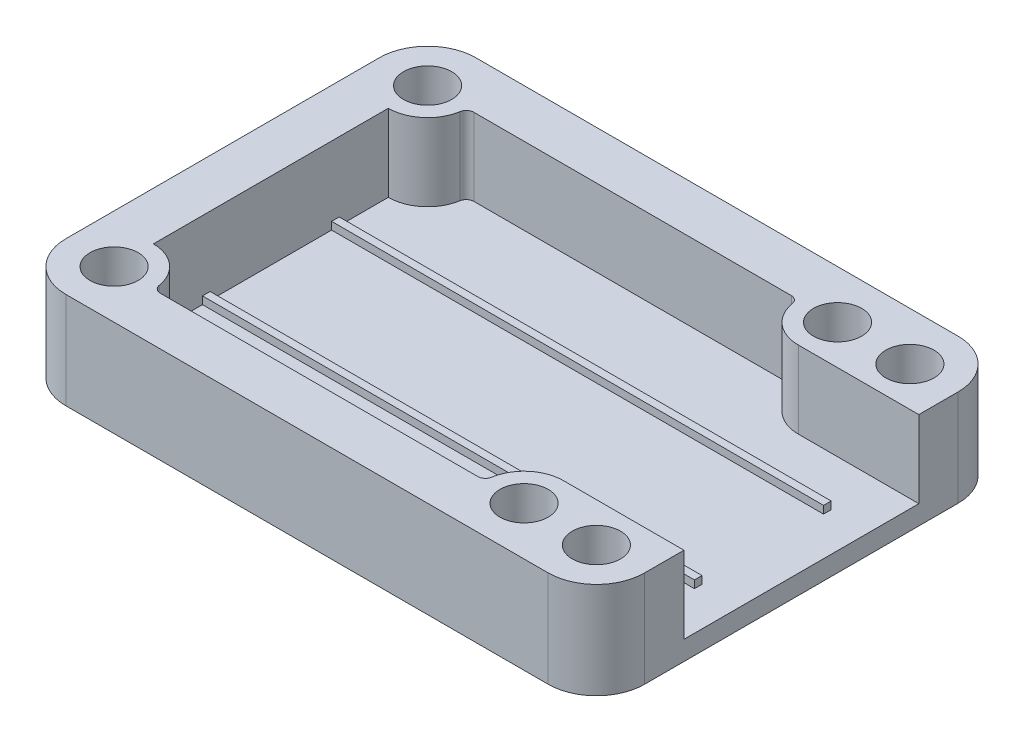
SolidWorks part; units mm, degrees
ref_plane "Front Plane" through (0, 0, 0) normal (0, 0, 1) x (1, 0, 0)
ref_plane "Top Plane" through (0, 0, 0) normal (0, 1, 0) x (1, 0, 0)
ref_plane "Right Plane" through (0, 0, 0) normal (1, 0, 0) x (0, 0, -1)
sketch "Main Body Sketch" plane through (0, 0, 0) normal (0, 1, 0) x (1, 0, 0)
  line L0 (-38.1, 26.9875) -> (38.1, 26.9875)
  line L1 (38.1, 26.9875) -> (38.1, -26.9875)
  line L2 (38.1, -26.9875) -> (-38.1, -26.9875)
  line L3 (-38.1, -26.9875) -> (-38.1, 26.9875)
  dimension "D1" = 76.2
  dimension "D2" = 53.975
  dimension "D3" = 38.1
  dimension "D4" = 26.9875
extrude "Main Body" add sketch "Main Body Sketch" along normal blind 12.7
sketch "Mounting Holes Sketch" plane through (0, 12.7, 0) normal (0, 1, 0) x (1, 0, 0)
  line L0 (38.1, -26.9875) -> (38.1, 26.9875) construction
  line L1 (-38.1, -26.9875) -> (38.1, -26.9875) construction
  line L2 (-38.1, 26.9875) -> (-38.1, -26.9875) construction
  line L3 (38.1, 26.9875) -> (-38.1, 26.9875) construction
  circle A0 centre (31.75, -20.6375) radius 3.175
  circle A1 centre (22.225, -20.6375) radius 3.175
  circle A2 centre (-31.75, -20.6375) radius 3.175
  circle A3 centre (31.75, 20.6375) radius 3.175
  circle A4 centre (22.225, 20.6375) radius 3.175
  circle A5 centre (-31.75, 20.6375) radius 3.175
  dimension "D1" = 6.35
  dimension "D3" = 6.35
  dimension "D7" = 6.35
  dimension "D11" = 6.35
  dimension "D12" = 6.35
  dimension "D13" = 6.35
  dimension "D2" = 6.35
  dimension "D5" = 6.35
  dimension "D4" = 6.35
  dimension "D6" = 9.525
  dimension "D8" = 6.35
  dimension "D9" = 6.35
  dimension "D10" = 53.975
  dimension "D14" = 6.35
  dimension "D15" = 6.35
  dimension "D16" = 6.35
  dimension "D17" = 9.525
  dimension "D18" = 6.35
  dimension "D19" = 6.35
extrude "Mounting Holes" cut sketch "Mounting Holes Sketch" against normal through all both and the other way through all
sketch "Main Cutout Sketch" plane through (0, 12.7, 0) normal (0, 1, 0) x (1, 0, 0)
  line L0 (31.75, -15.4625) -> (38.1, -15.4625)
  line L1 (38.1, -26.9875) -> (38.1, 26.9875) construction
  line L2 (31.75, -15.4625) -> (22.225, -15.4625)
  line L4 (-31.75, -15.4625) -> (-31.75, 15.4625)
  line L5 (22.225, 15.4625) -> (38.1, 15.4625)
  line L6 (38.1, 15.4625) -> (38.1, -15.4625)
  line L7 (-26.575, -20.6375) -> (17.05, -20.6375)
  line L8 (-38.1, 26.9875) -> (-38.1, -26.9875) construction
  line L11 (-38.1, -26.9875) -> (38.1, -26.9875) construction
  line L12 (17.05, 20.6375) -> (-26.575, 20.6375)
  circle A12 centre (-31.75, -20.6375) radius 5.175
  arc A15 (-26.575, -20.6375) -> (-31.75, -15.4625) centre (-31.75, -20.6375) ccw
  circle A20 centre (22.225, -20.6375) radius 5.175
  arc A21 (22.225, -15.4625) -> (17.05, -20.6375) centre (22.225, -20.6375) ccw
  circle A24 centre (-31.75, 20.6375) radius 5.175
  arc A25 (-31.75, 15.4625) -> (-26.575, 20.6375) centre (-31.75, 20.6375) ccw
  circle A27 centre (22.225, 20.6375) radius 5.175
  arc A28 (17.05, 20.6375) -> (22.225, 15.4625) centre (22.225, 20.6375) ccw
  dimension "D7" = 6.35
  dimension "D5" = 6.35
  dimension "D1" = 2
  dimension "D2" = 2
  dimension "D3" = 2
  dimension "D4" = 2
extrude "Main Cutout" cut sketch "Main Cutout Sketch" against normal offset from surface (10.16 mm away) 2.54 up to face at (31.75, 0, -17.4625)
sketch "Rib Sketch" plane through (0, 2.54, 0) normal (0, 1, 0) x (1, 0, 0)
  line L0 (-31.75, 0) -> (33.02, 0) construction
  line L1 (-31.75, -9) -> (33.02, -9)
  line L3 (33.02, -8) -> (-31.75, -8)
  line L5 (-31.75, 8) -> (33.02, 8)
  line L7 (33.02, 9) -> (-31.75, 9)
  line L9 (-31.75, -9) -> (-31.75, -8)
  line L10 (33.02, -9) -> (33.02, -8)
  line L11 (38.1, -15.4625) -> (38.1, 15.4625) construction
  line L12 (-31.75, 15.4625) -> (-31.75, -15.4625) construction
  line L13 (-31.75, 8) -> (-31.75, 9)
  line L14 (33.02, 8) -> (33.02, 9)
  dimension "D1" = 1
  dimension "D2" = 1
  dimension "D3" = 8
  dimension "D4" = 8
  dimension "D5" = 5.08
  dimension "D6" = 0
extrude "Rib" add sketch "Rib Sketch" along normal blind 1
fillet "Outer Corner Fillet" radius 6.35 4 edges at (38.1, 6.35, -26.9875) (38.1, 6.35, 26.9875) (-38.1, 6.35, 26.9875) (-38.1, 6.35, -26.9875)
fillet "Inner Corner Fillet" radius 1 4 edges at (17.05, 7.62, 20.6375) (-26.575, 7.62, 20.6375) (17.05, 7.62, -20.6375) (-26.575, 7.62, -20.6375)
equation "\"D3@Main Body Sketch\" = 0.5 * \"D1@Main Body Sketch\""
equation "\"D4@Main Body Sketch\" = 0.5 * \"D2@Main Body Sketch\""
equation "\"D3@Mounting Holes Sketch\" = \"D1@Mounting Holes Sketch\""
equation "\"D4@Mounting Holes Sketch\" = \"D5@Mounting Holes Sketch\""
equation "\"D6@Mounting Holes Sketch\" = 2.5in - 2.125in"
equation "\"D7@Mounting Holes Sketch\" = \"D1@Mounting Holes Sketch\""
equation "\"D8@Mounting Holes Sketch\" = \"D5@Mounting Holes Sketch\""
equation "\"D9@Mounting Holes Sketch\" = \"D5@Mounting Holes Sketch\""
equation "\"D11@Mounting Holes Sketch\" = \"D1@Mounting Holes Sketch\""
equation "\"D12@Mounting Holes Sketch\" = \"D1@Mounting Holes Sketch\""
equation "\"D13@Mounting Holes Sketch\" = \"D1@Mounting Holes Sketch\""
equation "\"D14@Mounting Holes Sketch\" = \"D5@Mounting Holes Sketch\""
equation "\"D15@Mounting Holes Sketch\" = \"D2@Mounting Holes Sketch\""
equation "\"D16@Mounting Holes Sketch\" = \"D4@Mounting Holes Sketch\""
equation "\"D17@Mounting Holes Sketch\" = \"D6@Mounting Holes Sketch\""
equation "\"D18@Mounting Holes Sketch\" = \"D8@Mounting Holes Sketch\""
equation "\"D19@Mounting Holes Sketch\" = \"D9@Mounting Holes Sketch\""
equation "\"D2@Rib Sketch\" = \"D1@Rib Sketch\""
equation "\"D4@Rib Sketch\" = \"D3@Rib Sketch\""
equation "\"D7@Main Cutout Sketch\"=\"D5@Main Cutout Sketch\""
